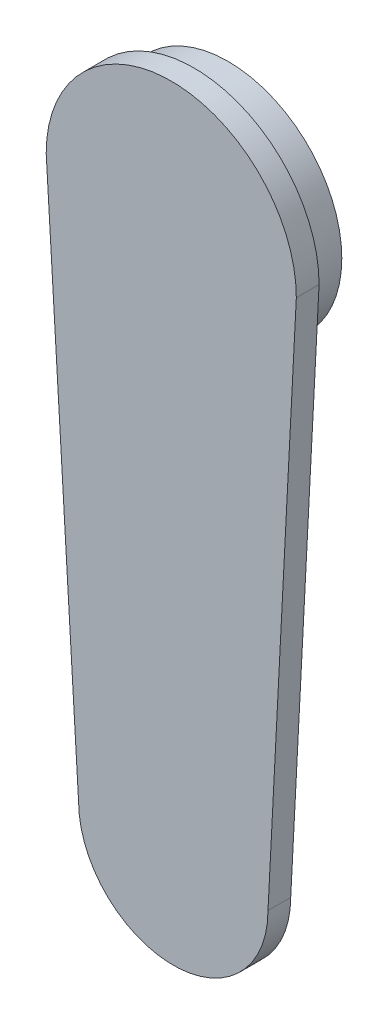
SolidWorks part; units mm, degrees
ref_plane "Front Plane" through (0, 0, 0) normal (0, 0, 1) x (1, 0, 0)
ref_plane "Top Plane" through (0, 0, 0) normal (0, 1, 0) x (1, 0, 0)
ref_plane "Right Plane" through (0, 0, 0) normal (1, 0, 0) x (0, 0, -1)
sketch "Sketch1" plane through (0, 0, 0) normal (0, 0, 1) x (1, 0, 0)
  line L1 (-55, 0) -> (-40.7681, -239.6759)
  line L2 (42.5319, -239.6759) -> (55, 0)
  circle A0 centre (0, 0) radius 55
  circle A1 centre (0.8819, -239.6759) radius 41.65
extrude "Boss-Extrude1" add sketch "Sketch1" along normal blind 10 and the other way blind 0.0001 contours L2 A0 L1 | A1 L2 A0 L1 | A1 L2
sketch "Sketch2" plane through (0, 0, -0.0001) normal (0, 0, -1) x (-1, 0, 0)
  circle A0 centre (0, 0) radius 50
extrude "Boss-Extrude2" add sketch "Sketch2" along normal blind 15
